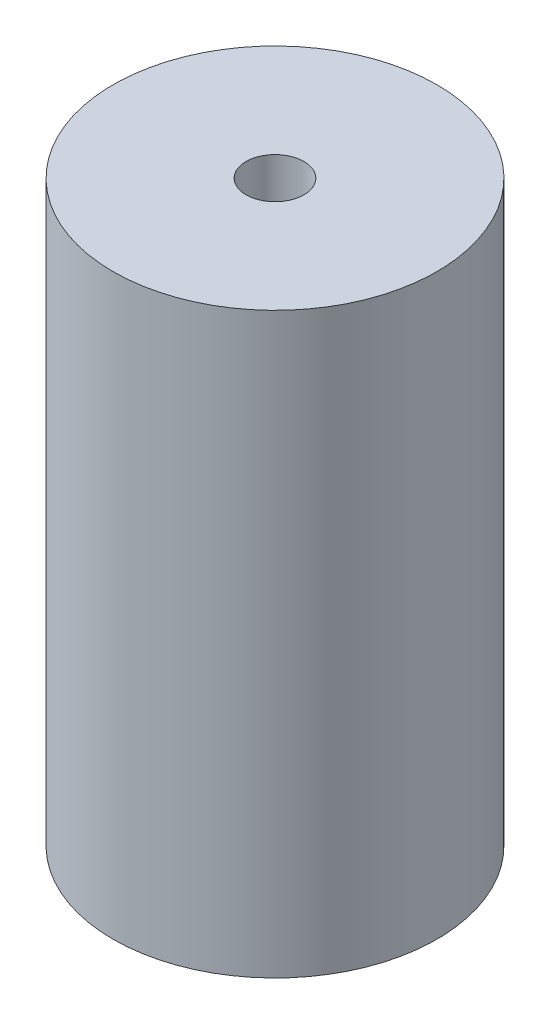
SolidWorks part; units mm, degrees
ref_plane "Front Plane" through (0, 0, 0) normal (0, 0, 1) x (1, 0, 0)
ref_plane "Top Plane" through (0, 0, 0) normal (0, 1, 0) x (1, 0, 0)
ref_plane "Right Plane" through (0, 0, 0) normal (1, 0, 0) x (0, 0, -1)
sketch "Sketch1" plane through (0, 0, 0) normal (0, 1, 0) x (1, 0, 0)
  circle A0 centre (0, 0) radius 14
  circle A1 centre (0, 0) radius 2.5
  dimension "D1" = 5
  dimension "D2" = 28
extrude "Boss-Extrude1" add sketch "Sketch1" along normal blind 50
